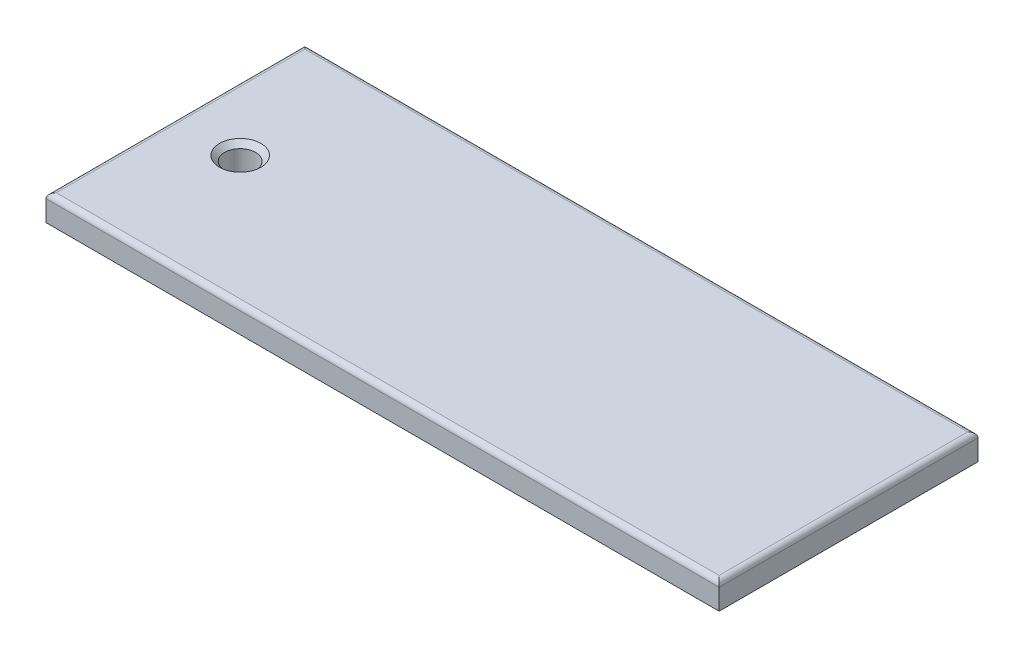
SolidWorks part; units mm, degrees
ref_plane "Front Plane" through (0, 0, 0) normal (0, 0, 1) x (1, 0, 0)
ref_plane "Top Plane" through (0, 0, 0) normal (0, 1, 0) x (1, 0, 0)
ref_plane "Right Plane" through (0, 0, 0) normal (1, 0, 0) x (0, 0, -1)
sketch "Sketch1" plane through (0, 0, 0) normal (0, 1, 0) x (1, 0, 0)
  line L1 (130, -50) -> (-130, -50)
  line L2 (130, -50) -> (130, 50)
  line L3 (130, 50) -> (-130, 50)
  line L4 (-130, -50) -> (-130, 50)
  line L5 (0, 50) -> (0, -50) construction
  line L6 (130, 0) -> (-130, 0) construction
  point P0 (0, 0)
  dimension "D1" = 260
  dimension "D2" = 100
extrude "Boss-Extrude1" add sketch "Sketch1" along normal blind 10
fillet "Fillet1" radius 2 4 edges at (-130, 10, 0) (0, 10, -50) (130, 10, 0) (0, 10, 50)
sketch "Sketch2" plane through (0, 10, 0) normal (0, 1, 0) x (1, 0, 0)
  line L0 (-130, -50) -> (-130, 50) construction
  circle A0 centre (-105, 0) radius 6
  dimension "D2" = 12
  dimension "D1" = 25
extrude "Cut-Extrude1" cut sketch "Sketch2" against normal through all
chamfer "Chamfer1" distance 2 angle 45 1 edges at (-105, 10, 6)
